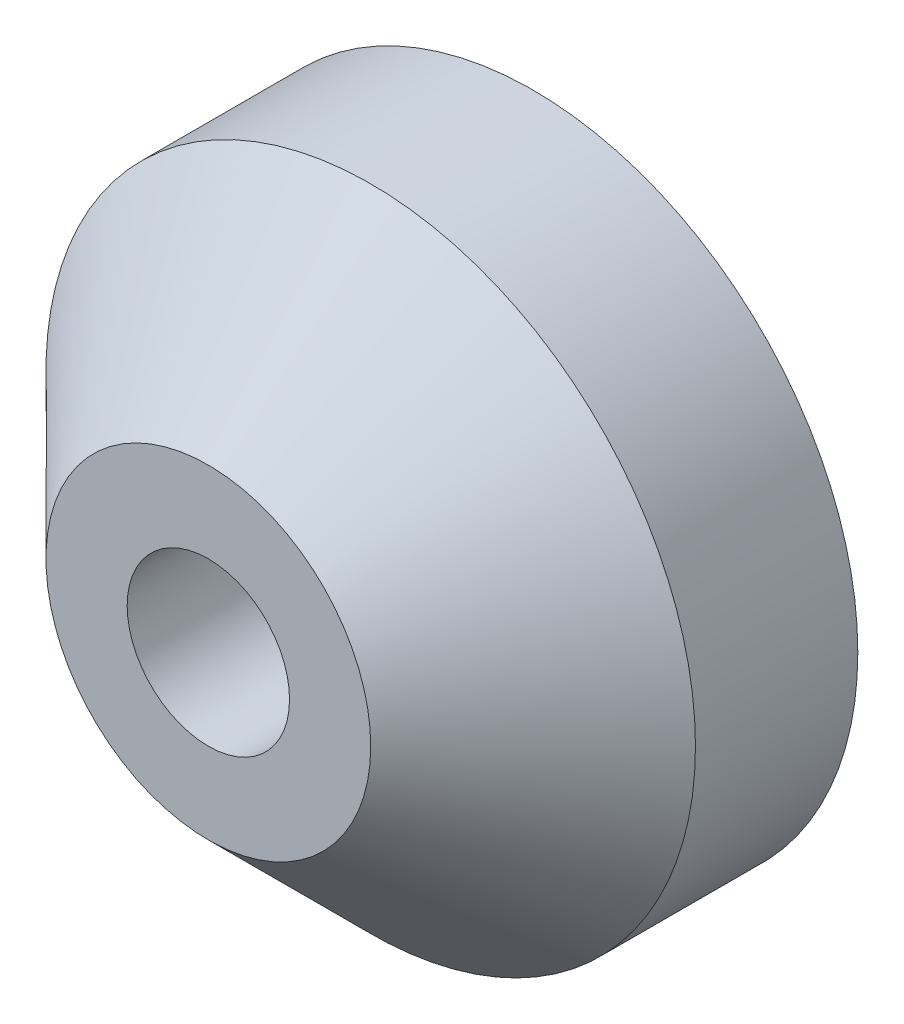
SolidWorks part; units mm, degrees
ref_plane "Front Plane" through (0, 0, 0) normal (0, 0, 1) x (1, 0, 0)
ref_plane "Top Plane" through (0, 0, 0) normal (0, 1, 0) x (1, 0, 0)
ref_plane "Right Plane" through (0, 0, 0) normal (1, 0, 0) x (0, 0, -1)
sketch "Sketch1" plane through (0, 0, 0) normal (0, 0, 1) x (1, 0, 0)
  circle A0 centre (0, 0) radius 5
  circle A1 centre (0, 0) radius 1.25
  dimension "D1" = 2.5
  dimension "D2" = 10
extrude "Boss-Extrude1" add sketch "Sketch1" along normal blind 5
chamfer "Chamfer1" distance 2.5 angle 45 1 edges at (5, 0, 5)
sketch "Sketch2" plane through (0, 0, 0) normal (0, 0, -1) x (-1, 0, 0)
  circle A0 centre (0, 0) radius 2.5
  dimension "D1" = 5
extrude "Cut-Extrude1" cut sketch "Sketch2" against normal blind 2
